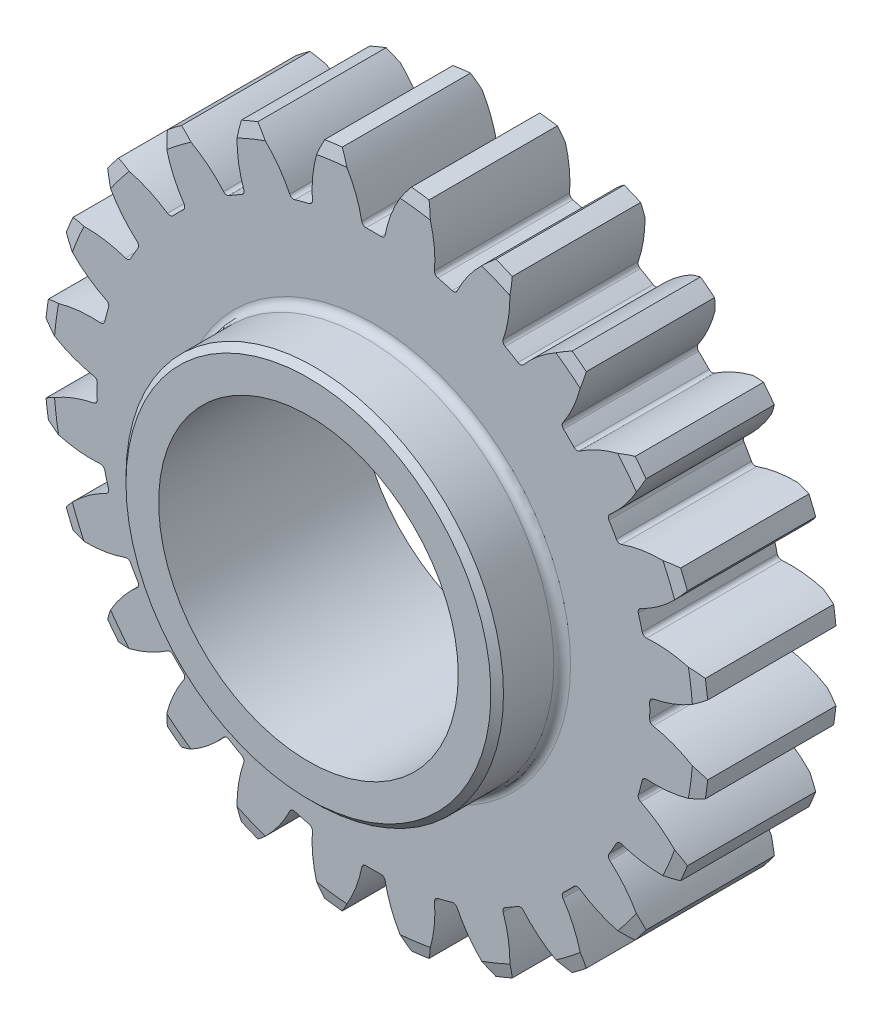
SolidWorks part; units mm, degrees
material "Aço carbono simples"
ref_plane "Plano frontal" through (0, 0, 0) normal (0, 0, 1) x (1, 0, 0)
ref_plane "Plano superior" through (0, 0, 0) normal (0, 1, 0) x (1, 0, 0)
ref_plane "Plano direito" through (0, 0, 0) normal (1, 0, 0) x (0, 0, -1)
sketch "Esboço1" plane through (0, 0, 0) normal (0, 1, 0) x (1, 0, 0)
  line L0 (0, 3.0496) -> (0, -3.0496)
  line L1 (-20, 12) -> (-20, -12)
  line L2 (-20, 0) -> (0, 0)
sketch "Esboço2" plane through (0, 0, 0) normal (1, 0, 0) x (0, 0, -1)
  line L0 (-1000, 0) -> (49000, 0) construction
  line L1 (-31.6, 0) -> (16.1, 0)
  line L2 (-16.1, 45) -> (-31.6, 45)
  line L3 (16.1, 79.2905) -> (-16.1, 79.2905)
  line L4 (-16.1, 79.2905) -> (-16.1, 45)
  line L5 (16.1, 0) -> (16.1, 79.2905)
  line L6 (-31.6, 45) -> (-31.6, 0)
  line L7 (0, 79.2905) -> (0, 0) construction
  dimension "D1" = 15.5
  dimension "D2" = 90
revolve "Revolução1" add sketch "Esboço2" angle 360 about L0
chamfer "Chanfro1" distance 3 angle 15 1 edges at (79.2905, 0, 16.1)
chamfer "Chanfro2" distance 3 angle 15 1 edges at (79.2905, 0, -16.1)
sketch "Esboço3" plane through (0, 0, 16.1) normal (0, 0, 1) x (1, 0, 0)
  line L0 (0, 0) -> (0, 88.0743) construction
  circle A0 centre (0, 0) radius 73.1912 construction
  circle A1 centre (0, 0) radius 68.7773 construction
  arc A2 (1.7629, 65.8485) -> (-1.7629, 65.8485) centre (0, 0) ccw
  circle A3 centre (0, 0) radius 79.2905 construction
  arc A4 (8.2432, 78.8609) -> (-8.2432, 78.8609) centre (0, 0) ccw
  arc A5 (-8.2432, 78.8609) -> (-4.7904, 73.0343) centre (-31.5339, 61.1222) cw
  arc A6 (-4.7904, 73.0343) -> (-2.7882, 66.672) centre (-31.5339, 61.1222) cw
  arc A7 (8.2432, 78.8609) -> (4.7904, 73.0343) centre (31.5339, 61.1222) ccw
  arc A8 (4.7904, 73.0343) -> (2.7882, 66.672) centre (31.5339, 61.1222) ccw
  arc A9 (-2.7882, 66.672) -> (-1.7629, 65.8485) centre (-1.7901, 66.8647) ccw
  arc A10 (2.7882, 66.672) -> (1.7629, 65.8485) centre (1.7901, 66.8647) cw
  point P17 (-2.6366, 65.8193)
  point P20 (2.6366, 65.8193)
extrude "Corte-extrusão1" cut sketch "Esboço3" against normal through all
pattern_circular "PadrãoCircular1" count 24 over 360 about axis through (0, 0, 0) along (0, 0, 1) of "Corte-extrusão1"
sketch "Esboço5" plane through (0, 0, 31.6) normal (0, 0, 1) x (1, 0, 0)
  circle A0 centre (0, 0) radius 35
  dimension "D1" = 70
extrude "Corte-extrusão3" cut sketch "Esboço5" against normal blind 25
chamfer "Chanfro3" distance 1.5 angle 45 1 edges at (45, 0, 31.6)
fillet "Filete2" radius 2 1 edges at (45, 0, 16.1)
scale "Escala1" scale about centroid uniform scaling yes scale factor 0.7
sketch "Esboço6" plane through (0, 0, 4.9036) normal (0, 0, 1) x (1, 0, 0)
  circle A0 centre (0, 0) radius 25
  dimension "D1" = 50
extrude "Corte-extrusão4" cut sketch "Esboço6" against normal through all and the other way through all
sketch "Esboço7" plane through (0, 0, 11.5536) normal (0, 0, 1) x (1, 0, 0)
  circle A0 centre (0, 0) radius 46.5
  dimension "D1" = 93
equation "\"diam_prim@Esboço3\" = \"módulo@Esboço1\"  *  \"n_dentes@Esboço1\""
equation "\"diam_ext@Esboço2\" = (\"módulo@Esboço1\"  *  \"n_dentes@Esboço1\") + 2  *  \"módulo@Esboço1\""
equation "\"diam_int@Esboço3\" = \"módulo@Esboço1\"  *   ( \"n_dentes@Esboço1\"  -  2.4 ) "
equation "\"diam_base@Esboço3\" = \"diam_prim@Esboço3\"  *   cos( \"ang_pressão@Esboço1\" ) "
equation "\"raio_flanco@Esboço3\" = (\"módulo@Esboço1\"  /  5 )   *  \"n_dentes@Esboço1\""
equation "\"vão_prim@Esboço3\" = \"módulo@Esboço1\"  *   pi  * 0.5"
equation "\"R1@Esboço3\" = \"módulo@Esboço1\"  /  6"
equation "\"ZT@PadrãoCircular1\" = \"n_dentes@Esboço1\""
